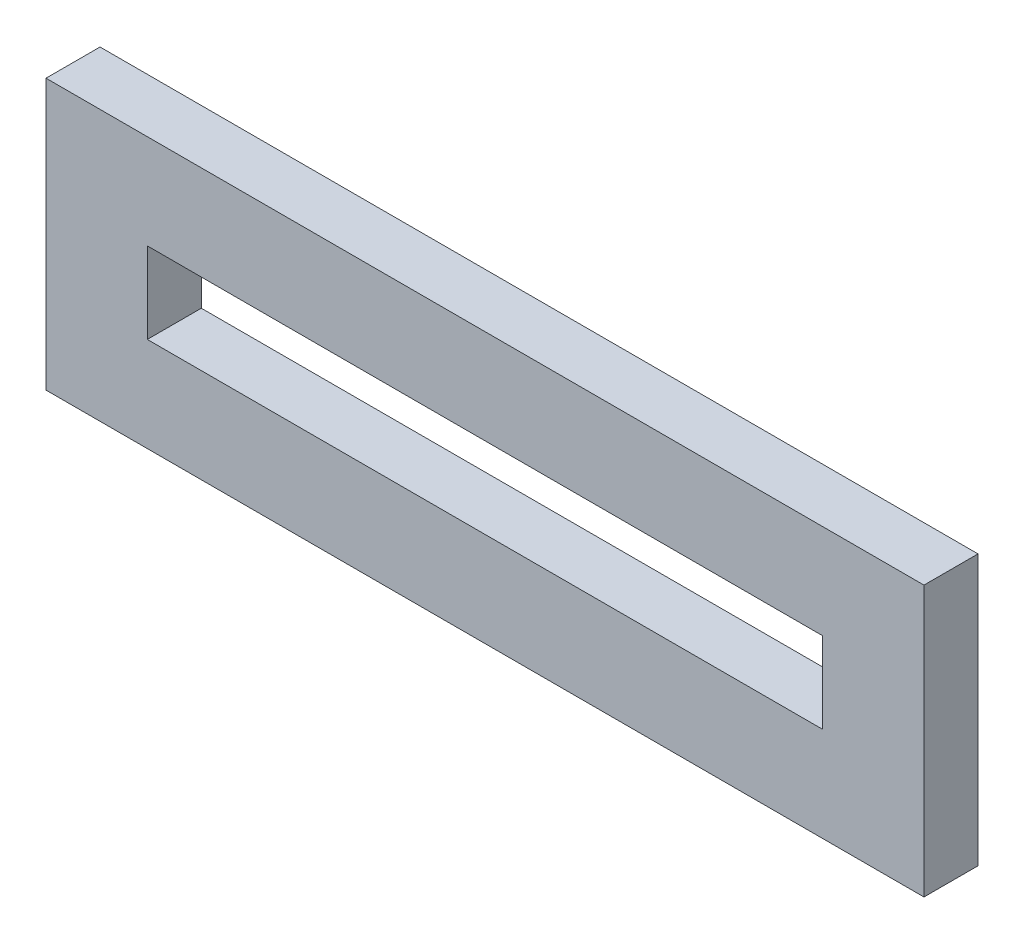
SolidWorks part; units mm, degrees
ref_plane "Front Plane" through (0, 0, 0) normal (0, 0, 1) x (1, 0, 0)
ref_plane "Top Plane" through (0, 0, 0) normal (0, 1, 0) x (1, 0, 0)
ref_plane "Right Plane" through (0, 0, 0) normal (1, 0, 0) x (0, 0, -1)
sketch "Sketch2" plane through (0, 0, 0) normal (0, 0, 1) x (1, 0, 0)
  line L1 (-32.5, -10) -> (32.5, -10)
  line L2 (-32.5, -10) -> (-32.5, 10)
  line L3 (-32.5, 10) -> (32.5, 10)
  line L4 (32.5, -10) -> (32.5, 10)
  line L5 (-32.5, -10) -> (32.5, 10) construction
  line L6 (-32.5, 10) -> (32.5, -10) construction
  point P0 (0, 0)
  dimension "D1" = 65
  dimension "D2" = 20
extrude "Boss-Extrude1" add sketch "Sketch2" along normal blind 4
sketch "Sketch3" plane through (0, 0, 0) normal (0, 0, 1) x (1, 0, 0)
  line L1 (25, 3) -> (-25, 3)
  line L2 (25, 3) -> (25, -3)
  line L3 (25, -3) -> (-25, -3)
  line L4 (-25, 3) -> (-25, -3)
  line L5 (25, 3) -> (-25, -3) construction
  line L6 (25, -3) -> (-25, 3) construction
  point P0 (0, 0)
  dimension "D1" = 6
  dimension "D2" = 50
extrude "Cut-Extrude1" cut sketch "Sketch3" along normal blind 10
